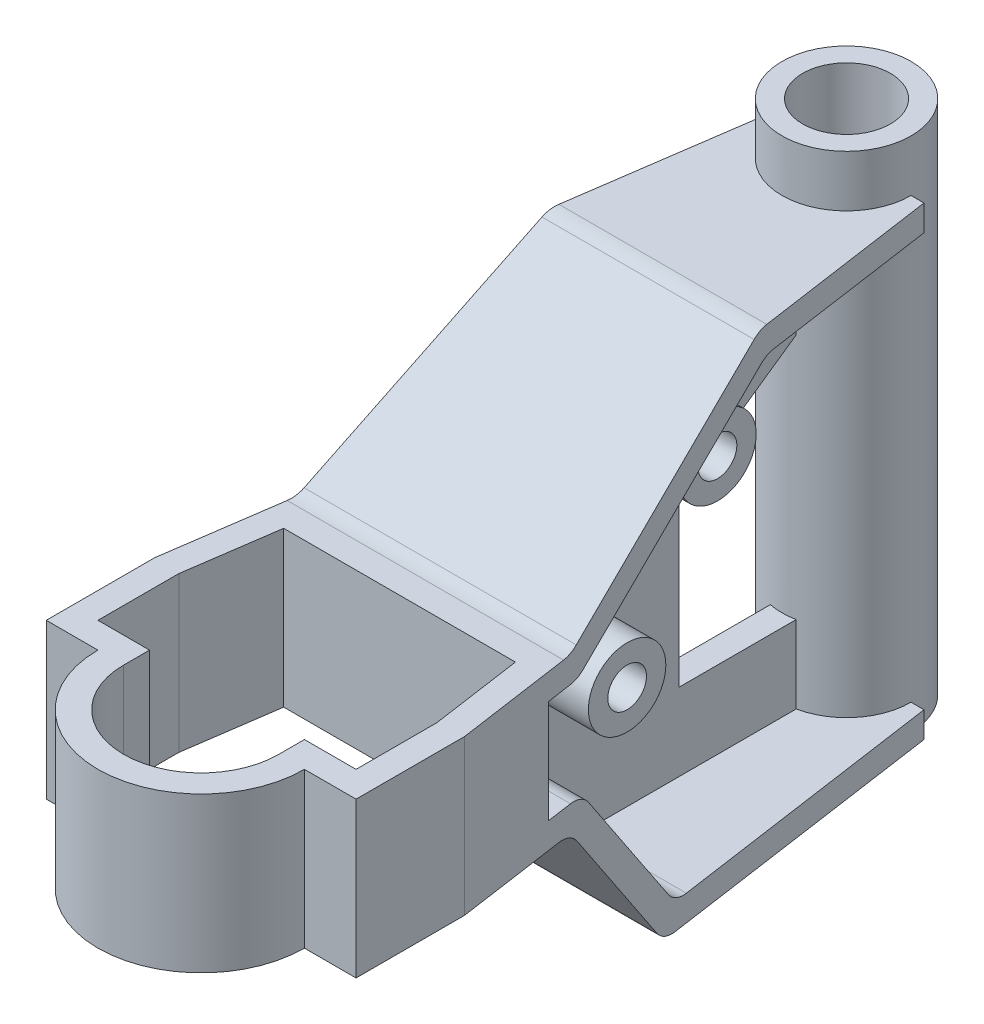
SolidWorks part; units mm, degrees
other "Markup1"
sketch "Sketch10" plane through (60, 140, 40) normal (0.6884, 0.3493, 0.6357) x (0.6614, 0.0575, -0.7479)
material "1060 Alloy"
ref_plane "Front Plane" through (0, 0, 0) normal (0, 0, 1) x (1, 0, 0)
ref_plane "Top Plane" through (0, 0, 0) normal (0, 1, 0) x (1, 0, 0)
ref_plane "Right Plane" through (0, 0, 0) normal (1, 0, 0) x (0, 0, -1)
sketch "Sketch1" plane through (0, 0, 0) normal (1, 0, 0) x (0, 0, -1)
  line L0 (0, 0) -> (0, 60)
  line L1 (0, 60) -> (90, 60)
  line L2 (90, 60) -> (175.6889, 120)
  line L3 (175.6889, 120) -> (250, 120)
  line L4 (250, 120) -> (250, 92.6829)
  line L5 (250, 92.6829) -> (180, 43.6683)
  line L6 (180, 43.6683) -> (180, -20)
  line L7 (180, -20) -> (250, -20)
  line L8 (250, -20) -> (250, -60)
  line L9 (250, -60) -> (132.0125, -60)
  line L10 (132.0125, -60) -> (90, 0)
  line L11 (90, 0) -> (0, 0)
  line L12 (250, 92.6829) -> (250, -20) construction
  line L13 (90, 60) -> (90, 0) construction
  dimension "D1" = 60
  dimension "D2" = 90
  dimension "D3" = 145
  dimension "D5" = 65
  dimension "D6" = 40
  dimension "D7" = 70
  dimension "D8" = 60
  dimension "D9" = 250
  dimension "D4" = 180
extrude "Boss-Extrude1" add sketch "Sketch1" along normal blind 60
sketch "Sketch2" plane through (0, 120, 0) normal (0, 1, 0) x (1, 0, 0)
  line L0 (60, 42.0348) -> (30, 250)
  line L1 (60, 90) -> (60, 0) construction
  line L2 (60, 250) -> (0, 250) construction
  line L3 (30, 250) -> (60, 250)
  line L4 (60, 250) -> (60, 42.0348)
extrude "Cut-Extrude1" cut sketch "Sketch2" against normal through all
sketch "Sketch4" plane through (0, 0, 0) normal (1, 0, 0) x (0, 0, -1)
  line L0 (80, 50) -> (80, 10)
  line L8 (250, -50) -> (137.2181, -50)
  line L9 (137.2181, -50) -> (95.2057, 10)
  line L10 (95.2057, 10) -> (42.0348, 10)
  line L11 (250, -50) -> (137.2181, -50)
  line L12 (137.2181, -50) -> (95.2057, 10)
  line L13 (95.2057, 10) -> (80, 10)
  line L14 (0, 60) -> (0, 0) construction
  line L15 (250, 110) -> (250, -50)
  line L17 (178.8419, 110) -> (250, 110)
  line L18 (93.153, 50) -> (178.8419, 110)
  line L19 (42.0348, 50) -> (93.153, 50)
  line L20 (178.8419, 110) -> (250, 110)
  line L21 (93.153, 50) -> (178.8419, 110)
  line L22 (80, 50) -> (93.153, 50)
  dimension "D3" = 80
  dimension "D1" = 10
  dimension "D2" = 10
extrude "Cut-Extrude2" cut sketch "Sketch4" along normal up to next from offset 5
fillet "Fillet1" radius 10 8 edges at (20.3599, 120, -175.6889) (26.5404, 60, -90) (22.6325, 110, -178.8419) (28.813, 50, -93.153) (23.5101, -60, -132.0125) (26.5404, 0, -90) (25.6347, -50, -137.2181) (28.6649, 10, -95.2057)
sketch "Sketch8" plane through (0, 60, 0) normal (0, 1, 0) x (1, 0, 0)
  line L0 (0, 0) -> (0, -40)
  line L1 (0, 0) -> (40, 0)
  arc A0 (0, -40) -> (40, 0) centre (0, 0) ccw
  dimension "D1" = 40
extrude "Boss-Extrude4" add sketch "Sketch8" against normal up to surface (60 mm away) up to face at (34.7663, 0, -42.3247)
sketch "Sketch3" plane through (0, -60, 0) normal (0, -1, 0) x (1, 0, 0)
  line L0 (0, -275) -> (0, -225)
  arc A0 (0, -275) -> (0, -225) centre (0, -250) ccw
  dimension "D1" = 50
extrude "Boss-Extrude2" add sketch "Sketch3" against normal blind 200
sketch "Sketch5" plane through (0, 60, 0) normal (0, 1, 0) x (1, 0, 0)
  line L0 (40, 10) -> (30, 10)
  line L1 (30, 10) -> (30, 0)
  line L2 (0, 76.847) -> (0, -30)
  line L13 (40, 10) -> (50, 10)
  line L14 (50, 10) -> (50, 41.3172)
  line L20 (50, 41.3172) -> (44.8747, 76.847)
  line L21 (44.8747, 76.847) -> (0, 76.847)
  line L22 (40, 10) -> (50, 10)
  line L23 (50, 10) -> (50, 41.3172)
  line L24 (50, 41.3172) -> (44.8747, 76.847)
  line L25 (44.8747, 76.847) -> (0, 76.847)
  circle A0 centre (0, 250) radius 17
  arc A1 (0, 225) -> (0, 275) centre (0, 250) ccw construction
  arc A4 (0, -30) -> (30, 0) centre (0, 0) ccw
  arc A5 (0, -30) -> (30, 0) centre (0, 0) ccw
  dimension "D2" = 8
  dimension "D1" = 10
  dimension "D3" = 10
extrude "Cut-Extrude3" cut sketch "Sketch5" against normal through all both and the other way through all
sketch "Sketch6" plane through (5, 0, 0) normal (1, 0, 0) x (0, 0, -1)
  line L0 (0, 60) -> (0, 0) construction
  line L1 (0, 0) -> (42.0348, 0) construction
  circle A0 centre (175, 70) radius 15
  circle A1 centre (140, 10) radius 15
  dimension "D1" = 140
  dimension "D2" = 175
  dimension "D5" = 30
  dimension "D3" = 70
  dimension "D4" = 10
extrude "Boss-Extrude3" add sketch "Sketch6" along normal blind 20
sketch "Sketch7" plane through (25, 0, 0) normal (1, 0, 0) x (0, 0, -1)
  circle A0 centre (140, 10) radius 7.5
  circle A1 centre (175, 70) radius 7.5
  dimension "D1" = 15
extrude "Cut-Extrude4" cut sketch "Sketch7" against normal up to next
mirror "Mirror2" about plane through (0, 0, 0) normal (-1, 0, 0) of bodies 108
sketch "Sketch11" plane through (25, 0, 0) normal (1, 0, 0) x (0, 0, -1)
  circle A0 centre (175, 70) radius 12.7
  dimension "D1" = 25.4
equation "\"A\"= 60"
equation "\"B\"= 60"
equation "\"C\"= 100"
equation "\"D\"= 100"
equation "\"E\"= 100"
equation "\"X\"= \"A\" / 5"
equation "\"Y\"= \"C\" + 10"
equation "\"D1@Sketch1\"=\"A\""
equation "\"D4@Sketch1\"=\"A\" * 3"
equation "\"D1@Boss-Extrude1\"=\"B\""
equation "\"D1@Boss-Extrude2\"= \"A\" * 3 + 20"
